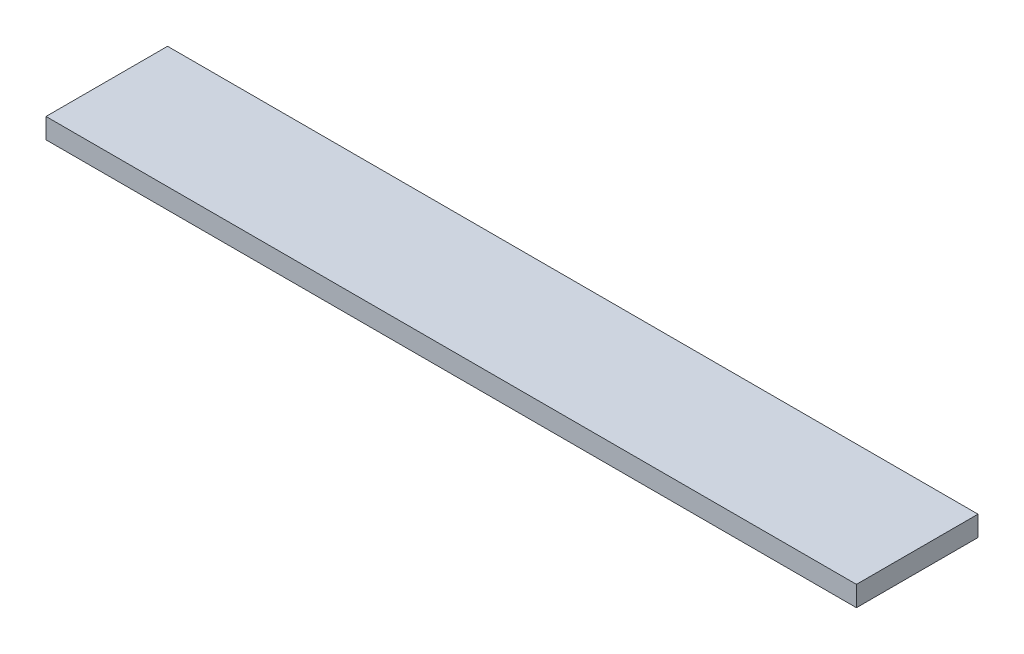
SolidWorks part; units mm, degrees
ref_plane "Front Plane" through (0, 0, 0) normal (0, 0, 1) x (1, 0, 0)
ref_plane "Top Plane" through (0, 0, 0) normal (0, 1, 0) x (1, 0, 0)
ref_plane "Right Plane" through (0, 0, 0) normal (1, 0, 0) x (0, 0, -1)
sketch "Sketch1" plane through (0, 0, 0) normal (0, 1, 0) x (1, 0, 0)
  line L1 (-40, -6) -> (40, -6)
  line L2 (-40, -6) -> (-40, 6)
  line L3 (-40, 6) -> (40, 6)
  line L4 (40, -6) -> (40, 6)
  line L5 (-40, -6) -> (40, 6) construction
  line L6 (-40, 6) -> (40, -6) construction
  point P0 (0, 0)
  dimension "D1" = 80
  dimension "D2" = 12
extrude "Boss-Extrude1" add sketch "Sketch1" along normal blind 2
